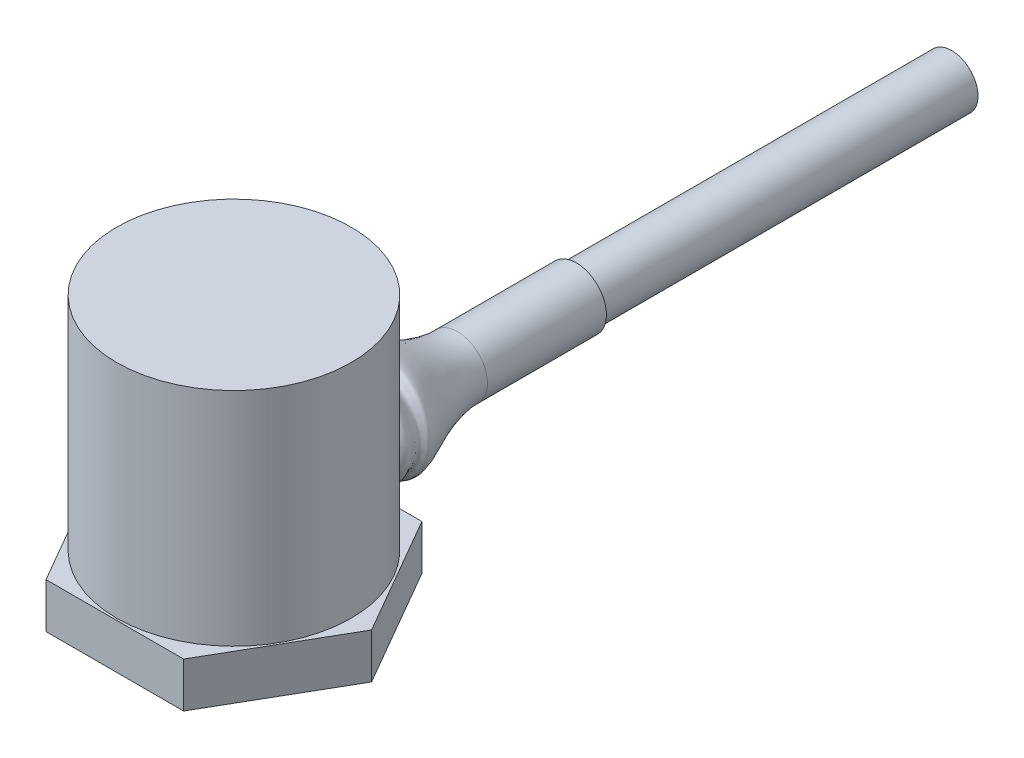
SolidWorks part; units mm, degrees
ref_plane "Płaszczyzna przednia" through (0, 0, 0) normal (0, 0, 1) x (1, 0, 0)
ref_plane "Płaszczyzna górna" through (0, 0, 0) normal (0, 1, 0) x (1, 0, 0)
ref_plane "Płaszczyzna prawa" through (0, 0, 0) normal (1, 0, 0) x (0, 0, -1)
sketch "Szkic1" plane through (0, 0, 0) normal (0, 1, 0) x (1, 0, 0)
  line L6 (-1.8331, 3.175) -> (1.8331, 3.175)
  line L7 (1.8331, 3.175) -> (3.6662, 0)
  line L8 (3.6662, 0) -> (1.8331, -3.175)
  line L9 (1.8331, -3.175) -> (-1.8331, -3.175)
  line L10 (-1.8331, -3.175) -> (-3.6662, 0)
  line L11 (-3.6662, 0) -> (-1.8331, 3.175)
  circle A0 centre (0, 0) radius 3.175
  point P12 (0, 0)
  dimension "D1" = 6.35
extrude "Dodanie-wyciągnięcie1" add sketch "Szkic1" along normal blind 1.2 contours A0 | A0 L10 L9 | A0 L9 L8 | A0 L8 L7 | A0 L11 L10 | A0 L6 L11 | A0 L7 L6
sketch "Szkic2" plane through (0, 1.2, 0) normal (0, 1, 0) x (1, 0, 0)
  circle A0 centre (0, 0) radius 3.125
  dimension "D1" = 6.25
extrude "Dodanie-wyciągnięcie2" add sketch "Szkic2" along normal blind 5.9 contours A0
sketch "Szkic3" plane through (0, 0, 0) normal (1, 0, 0) x (0, 0, -1)
  line L0 (2.625, 2.475) -> (9.125, 2.475)
  line L1 (3.125, 1.2) -> (3.125, 7.1) construction
  line L2 (9.125, 2.475) -> (9.125, 1.675)
  line L3 (2.625, 1.2) -> (2.625, 2.475)
  line L4 (2.625, 1.2) -> (3.125, 1.2)
  line L5 (5.9547, 1.675) -> (9.125, 1.675)
  spline S0 degree 3 poles (3.125, 1.2) (3.3023, 0.9946) (3.431, 1.2128) (3.7173, 1.2211) (3.7596, 1.0375) (4.0253, 1.0898) (4.6723, 1.3734) (5.3693, 1.6918) (5.9547, 1.675) knots 0 0 0 0 0.161889 0.198271 0.247726 0.302592 0.419245 1 1 1 1
  dimension "D1" = 0.8
  dimension "D2" = 6.5
revolve "Obrót6" add sketch "Szkic3" angle 360 about L0
sketch "Szkic4" plane through (0, 0, -9.125) normal (0, 0, -1) x (-1, 0, 0)
  circle A0 centre (0, 2.475) radius 0.7
  dimension "D1" = 1.4
extrude "Dodanie-wyciągnięcie3" add sketch "Szkic4" along normal blind 10
